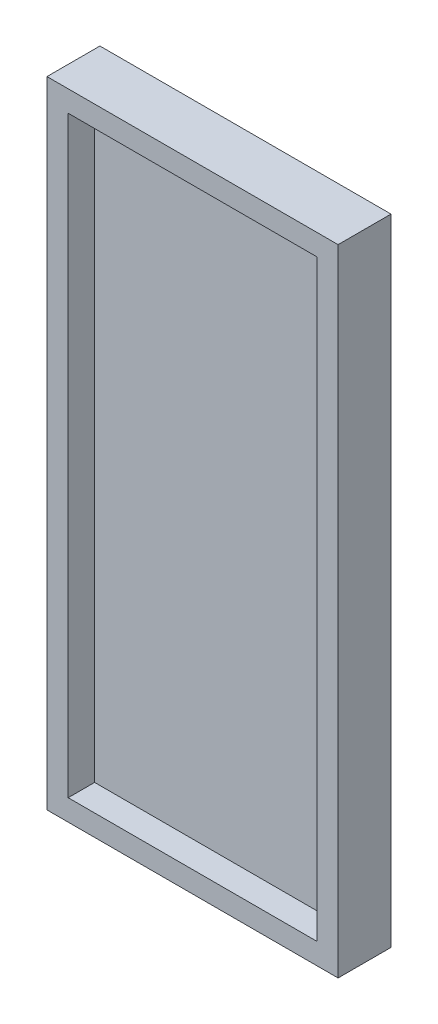
SolidWorks part; units mm, degrees
ref_plane "Front Plane" through (0, 0, 0) normal (1, 0, 0) x (0, 1, 0)
ref_plane "Top Plane" through (0, 0, 0) normal (0, 0, 1) x (0, 1, 0)
ref_plane "Right Plane" through (0, 0, 0) normal (0, 1, 0) x (-1, 0, 0)
sketch "Sketch1" plane through (0, 0, 0) normal (0, 0, 1) x (0, 1, 0)
  line L1 (0, 0) -> (120, 0)
  line L2 (0, 0) -> (0, 55)
  line L3 (0, 55) -> (120, 55)
  line L4 (120, 0) -> (120, 55)
  dimension "D1" = 120
  dimension "D2" = 55
extrude "Boss-Extrude1" add sketch "Sketch1" along normal blind 10
sketch "Sketch2" plane through (0, 0, 10) normal (0, 0, 1) x (1, 0, 0)
  line L14 (-51, 4) -> (-4, 4)
  line L15 (-4, 116) -> (-51, 116)
  line L16 (-4, 4) -> (-4, 116)
  line L17 (-51, 116) -> (-51, 4)
  line L18 (-51, 4) -> (-4, 4)
  line L19 (-4, 116) -> (-51, 116)
  line L20 (-4, 4) -> (-4, 116)
  line L21 (-51, 116) -> (-51, 4)
  dimension "D1" = 4
extrude "Cut-Extrude1" cut sketch "Sketch2" against normal blind 5
